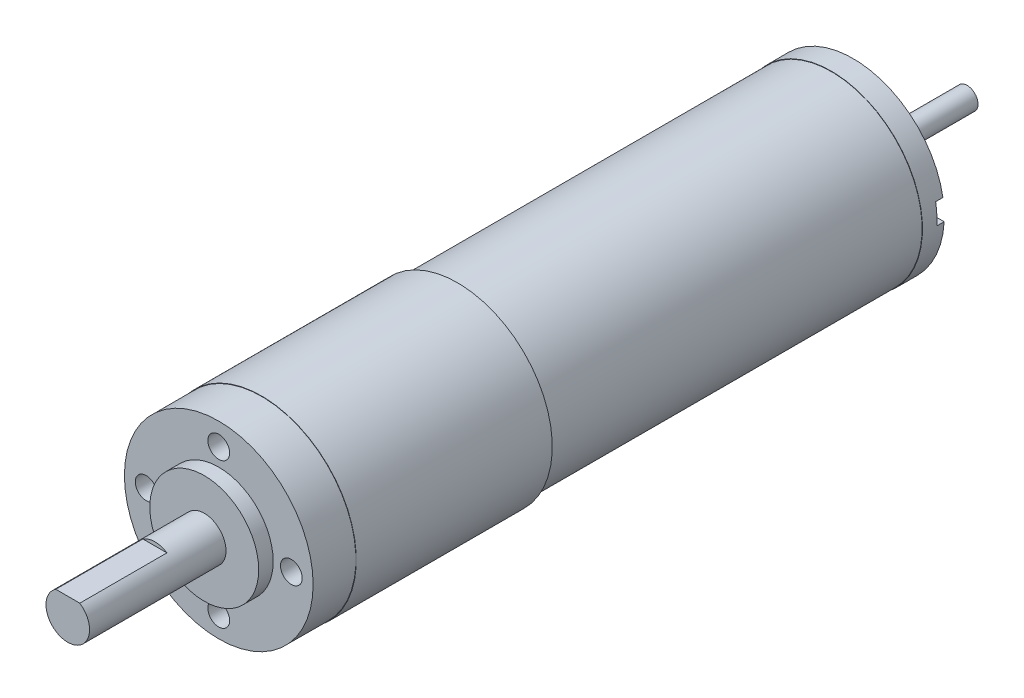
SolidWorks part; units mm, degrees
ref_plane "Plan de face" through (0, 0, 0) normal (0, 0, 1) x (1, 0, 0)
ref_plane "Plan de dessus" through (0, 0, 0) normal (0, 1, 0) x (1, 0, 0)
ref_plane "Plan de droite" through (0, 0, 0) normal (1, 0, 0) x (0, 0, -1)
sketch "Esquisse1" plane through (0, 0, 0) normal (0, 0, 1) x (1, 0, 0)
  circle A0 centre (0, 0) radius 12.5
  dimension "D1" = 25
extrude "Boss.-Extru.1" add sketch "Esquisse1" along normal blind 54.5
sketch "Esquisse2" plane through (0, 0, 0) normal (0, 0, -1) x (-1, 0, 0)
  circle A0 centre (0, 0) radius 4
  dimension "D1" = 8
extrude "Boss.-Extru.2" add sketch "Esquisse2" along normal blind 1.35
sketch "Esquisse3" plane through (0, 0, 0) normal (0, 0, -1) x (-1, 0, 0)
  circle A0 centre (0, 0) radius 1.5
  dimension "D1" = 3
extrude "Boss.-Extru.3" add sketch "Esquisse3" along normal blind 15.7
sketch "Esquisse4" plane through (0, 0, 54.5) normal (0, 0, 1) x (1, 0, 0)
  circle A0 centre (0, 0) radius 13
  dimension "D1" = 26
extrude "Boss.-Extru.4" add sketch "Esquisse4" along normal blind 32.9
sketch "Esquisse5" plane through (0, 0, 87.4) normal (0, 0, 1) x (1, 0, 0)
  circle A0 centre (0, 0) radius 7.5
  dimension "D1" = 15
extrude "Boss.-Extru.5" add sketch "Esquisse5" along normal blind 2
sketch "Esquisse7" plane through (0, 0, 87.4) normal (0, 0, 1) x (1, 0, 0)
  circle A0 centre (0, 0) radius 3
  dimension "D1" = 6
extrude "Boss.-Extru.6" add sketch "Esquisse7" along normal blind 20.8
sketch "Esquisse8" plane through (0, 0, 108.2) normal (0, 0, 1) x (1, 0, 0)
  line L0 (11.3409, -3) -> (-12.8581, -3) construction
  line L1 (-13.1918, 2.5) -> (13.1023, 2.5) construction
  line L3 (-5.5301, 2.5) -> (4.0781, 2.5)
  line L4 (-5.5301, 2.5) -> (-5.5301, 14.9404)
  line L5 (-5.5301, 14.9404) -> (4.0781, 14.9404)
  line L6 (4.0781, 2.5) -> (4.0781, 14.9404)
  circle A0 centre (0, 0) radius 3 construction
  dimension "D1" = 5.5
extrude "Enlèv. mat.-Extru.1" cut sketch "Esquisse8" against normal blind 12
sketch "Esquisse9" plane through (0, 0, 87.4) normal (0, 0, 1) x (1, 0, 0)
  line L0 (0, 25.9344) -> (0, -26.0822) construction
  line L1 (38.4614, 0) -> (-29.5545, 0) construction
  circle A0 centre (0, -0.0739) radius 10 construction
  circle A1 centre (-9.9997, 0) radius 1.5
  circle A2 centre (9.9997, 0) radius 1.5
  circle A3 centre (0, -10.0739) radius 1.5
  circle A4 centre (0, 9.9261) radius 1.5
  dimension "D1" = 20
  dimension "D2" = 3
extrude "Enlèv. mat.-Extru.2" cut sketch "Esquisse9" against normal blind 12
sketch "Esquisse10" plane through (0, 0, 54.5) normal (0, 0, -1) x (-1, 0, 0)
  circle A0 centre (0, 0) radius 13.05
  dimension "D1" = 26.1
extrude "Boss.-Extru.7" add sketch "Esquisse10" against normal blind 27
sketch "Esquisse11" plane through (0, 0, 0) normal (0, 0, -1) x (-1, 0, 0)
  circle A0 centre (0, 0) radius 12.55
  circle A1 centre (0, 0) radius 12.5 construction
  dimension "D1" = 0.05
extrude "Boss.-Extru.8" add sketch "Esquisse11" against normal blind 3
sketch "Esquisse12" plane through (0, 0, 0) normal (0, 0, -1) x (-1, 0, 0)
  line L0 (0, 37.4409) -> (0, -32.0434) construction
  line L1 (0, 0) -> (-29.4574, -17.0073) construction
  line L2 (0, 0) -> (34.7353, -20.0544) construction
  line L3 (21.8958, 0) -> (-25.9968, 0) construction
  line L4 (21.3434, 2.15) -> (10.0059, 2.15) construction
  line L5 (10.0059, 2.15) -> (10.0059, -0.65) construction
  line L6 (10.0059, -0.65) -> (21.8958, -0.65) construction
  line L7 (-21.8998, -0.65) -> (-10.0688, -0.65) construction
  line L8 (-10.0688, -0.65) -> (-10.0688, 2.15) construction
  line L9 (-10.0688, 2.15) -> (-23.9916, 2.15) construction
  line L10 (12.3645, 2.15) -> (10.0059, 2.15)
  line L11 (10.0059, 2.15) -> (10.0059, -0.65)
  line L12 (10.0059, -0.65) -> (12.5332, -0.65)
  line L13 (-12.5332, -0.65) -> (-10.0688, -0.65)
  line L14 (-10.0688, -0.65) -> (-10.0688, 2.15)
  line L15 (-10.0688, 2.15) -> (-12.3645, 2.15)
  line L16 (21.8958, 0.9) -> (5.0993, 0.9) construction
  circle A0 centre (0, 0) radius 8.5 construction
  circle A1 centre (0, 8.5) radius 1
  circle A2 centre (7.3612, -4.25) radius 1
  circle A3 centre (0, -8.5) radius 1
  circle A4 centre (-7.3612, -4.25) radius 1
  circle A5 centre (0, 0) radius 12.55 construction
  arc A6 (12.5332, -0.65) -> (12.3645, 2.15) centre (0, 0) ccw
  arc A7 (-12.3645, 2.15) -> (-12.5332, -0.65) centre (0, 0) ccw
  dimension "D3" = 17
  dimension "D4" = 2
  dimension "D1" = 60
  dimension "D2" = 60
  dimension "D5" = 2.8
  dimension "D6" = 0.9
  dimension "D7" = 2.15
  dimension "D8" = 0.65
extrude "Enlèv. mat.-Extru.4" cut sketch "Esquisse12" against normal blind 1
